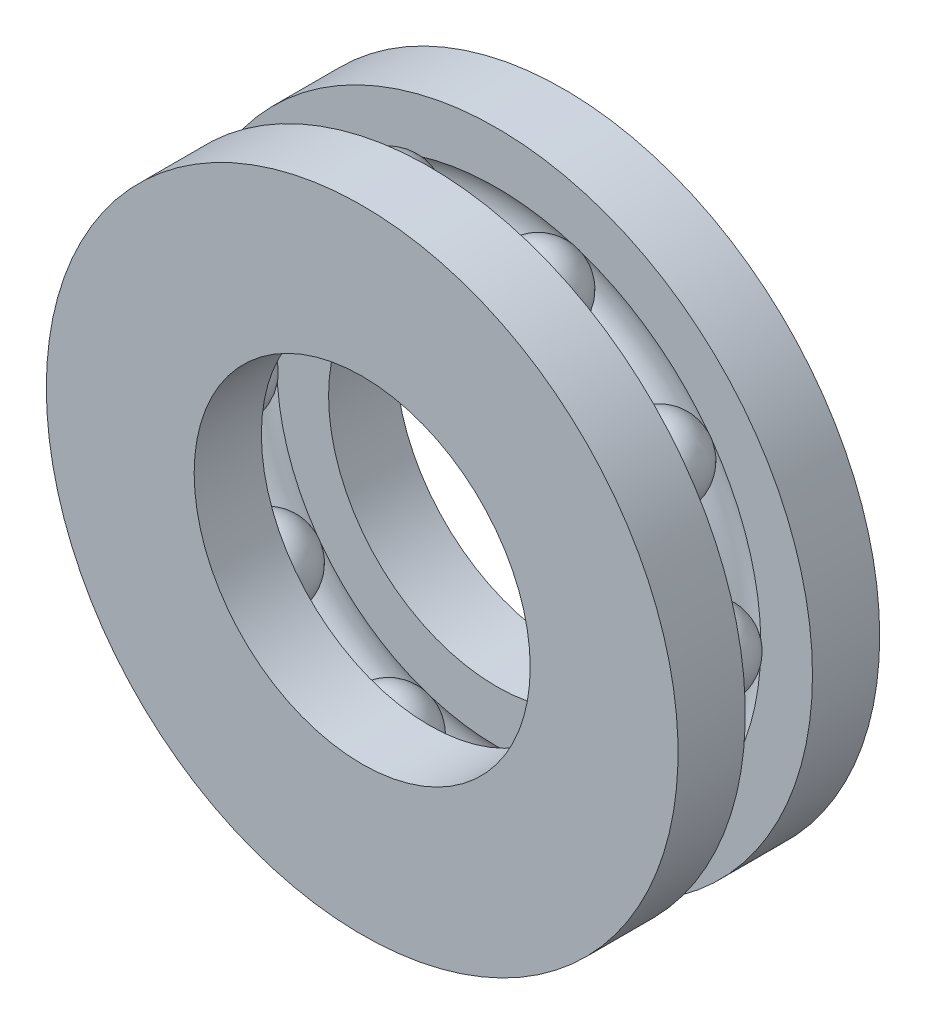
SolidWorks part; units mm, degrees
material "AISI 304"
ref_plane "Front Plane" through (0, 0, 0) normal (0, 0, 1) x (1, 0, 0)
ref_plane "Top Plane" through (0, 0, 0) normal (0, 1, 0) x (1, 0, 0)
ref_plane "Right Plane" through (0, 0, 0) normal (1, 0, 0) x (0, 0, -1)
sketch "Sketch1" plane through (0, 0, 0) normal (0, 0, 1) x (1, 0, 0)
  circle A0 centre (0, 0) radius 12.5
  circle A1 centre (0, 0) radius 23.5
  dimension "D1" = 47
  dimension "D2" = 25
extrude "Boss-Extrude1" add sketch "Sketch1" along normal blind 5
ref_plane "Plane1" through (0, 0, 15) normal (0, 0, -1) x (-1, 0, 0)
sketch "Sketch3" plane through (0, 0, 15) normal (0, 0, -1) x (-1, 0, 0)
  circle A0 centre (0, 0) radius 23.5 construction
  circle A1 centre (0, 0) radius 23.5
  circle A2 centre (0, 0) radius 12.5 construction
  circle A3 centre (0, 0) radius 12.5
extrude "Boss-Extrude2" add sketch "Sketch3" along normal blind 5 separate body
sketch "Sketch2" plane through (0, 0, 0) normal (0, 1, 0) x (1, 0, 0)
  line L0 (0, 0) -> (0, -12.3563) construction
  circle A0 centre (-18, -7.5) radius 3
  dimension "D1" = 6
  dimension "D2" = 18
  dimension "D3" = 7.5
revolve "Cut-Revolve1" cut sketch "Sketch2" angle 360 about L0
sketch "Sketch4" plane through (0, 0, 0) normal (0, 1, 0) x (1, 0, 0)
  line L0 (-18, -9.6788) -> (-18, 0.293) construction
  line L1 (-18, -10.51) -> (-18, -4.49)
  arc A2 (-18, -4.49) -> (-18, -10.51) centre (-18, -7.5) ccw
  dimension "D2" = 18
  dimension "D1" = 3.01
  dimension "D3" = 7.5
revolve "Revolve1" add sketch "Sketch4" angle 360 about L0
pattern_circular "CirPattern6" count 10 every 36 about axis through (0, 0, 0) along (0, 0, 1) of "Revolve1"
